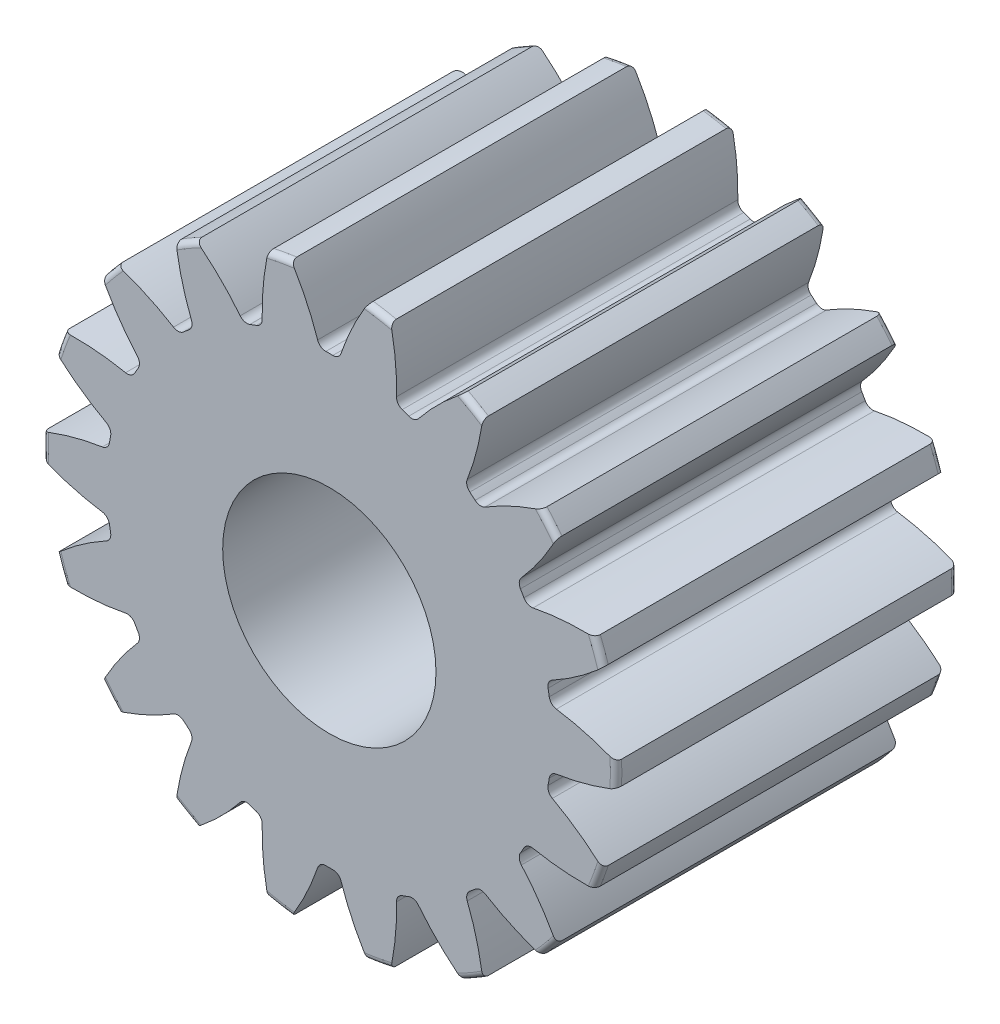
SolidWorks part; units mm, degrees
ref_plane "Front Plane" through (0, 0, 0) normal (0, 0, 1) x (1, 0, 0)
ref_plane "Top Plane" through (0, 0, 0) normal (0, 1, 0) x (1, 0, 0)
ref_plane "Right Plane" through (0, 0, 0) normal (1, 0, 0) x (0, 0, -1)
sketch "Sketch1" plane through (0, 0, 0) normal (0, 0, 1) x (1, 0, 0)
  line L0 (-228.6, 0) -> (228.6, 0) construction
  circle A0 centre (0, 0) radius 5.334 construction
  circle A1 centre (0, 0) radius 4.7625 construction
  circle A2 centre (0, 0) radius 4.1434 construction
  circle A3 centre (0, 0) radius 3.9751 construction
  circle A4 centre (0, 0) radius 1.9844 construction
  dimension "D2" = 0.5715
  dimension "D3" = 1.1906
  dimension "D1" = 1.1906
sketch "Sketch2" plane through (0, 0, 0) normal (1, 0, 0) x (0, 0, -1)
  line L0 (0, 0) -> (-3.175, 0) construction
  line L1 (-3.175, 0) -> (-9.525, 0) construction
  dimension "Overall Width" = 9.525
  dimension "Face Width" = 3.175
sketch "Sketch4" plane through (0, 0, 0) normal (1, 0, 0) x (0, 0, -1)
  line L0 (-9.525, 1.9844) -> (-9.525, 3.9751)
  line L1 (-9.525, 3.9751) -> (-6.35, 3.9751)
  line L2 (-6.35, 3.9751) -> (-6.35, 5.334)
  line L3 (-6.35, 5.334) -> (0, 5.334)
  line L4 (0, 5.334) -> (0, 1.9844)
  line L5 (-6.35, 3.9751) -> (-6.35, 0) construction
  line L6 (0, 5.334) -> (0, -5.334) construction
  line L7 (-6.35, 3.9751) -> (0, 3.9751) construction
  line L12 (-9.525, 1.9844) -> (0, 1.9844)
  dimension "D1" = 6.35
  dimension "D2" = 1.9844
revolve "Revolve1" add sketch "Sketch4" angle 360 about L1
fillet "Fillet2" radius 0.1067 4 edges at (0, 3.9751, 9.525) (0, 3.9751, 6.35) (0, 5.334, 6.35) (0, 5.334, 0)
sketch "Sketch7" plane through (0, 0, 6.35) normal (0, 0, 1) x (1, 0, 0)
  line L0 (0, 0) -> (0, 5.334) construction
  line L1 (0.4151, 4.7444) -> (0.6703, 5.2917) construction
  line L3 (0.9262, 5.253) -> (0.827, 4.6901) construction
  line L4 (0.827, 4.6901) -> (0.7195, 4.0804) construction
  line L5 (0, 0) -> (0.7195, 4.0804) construction
  line L6 (0.4151, 4.7444) -> (0, 0) construction
  line L7 (0.4151, 4.7444) -> (0.4649, 5.3137) construction
  line L8 (0.4151, 4.7444) -> (0, 0) construction
  circle A0 centre (0, 0) radius 5.334 construction
  arc A1 (-0.0648, 4.1429) -> (0.0648, 4.1429) centre (0, 0) cw
  circle A2 centre (0, 0) radius 4.1434 construction
  arc A3 (-0.4151, 4.7444) -> (0.4151, 4.7444) centre (0, 0) cw construction
  circle A4 centre (0, 0) radius 4.7625 construction
  arc A5 (1.139, 5.211) -> (0.712, 5.2863) centre (0, 0) ccw construction
  arc A6 (0.4151, 4.7444) -> (1.2326, 4.6002) centre (0, 0) cw construction
  arc A7 (-0.712, 5.2863) -> (0.712, 5.2863) centre (0, 0) cw
  arc A8 (0.2177, 4.251) -> (0.712, 5.2863) centre (4.7314, 2.7317) cw
  arc A9 (-0.2177, 4.251) -> (-0.712, 5.2863) centre (-4.7314, 2.7317) ccw
  arc A10 (-0.0648, 4.1429) -> (-0.2177, 4.251) centre (-0.0672, 4.3016) cw
  arc A11 (0.0648, 4.1429) -> (0.2177, 4.251) centre (0.0672, 4.3016) ccw
  point P26 (-0.1817, 4.1394)
  point P29 (0.1817, 4.1394)
  dimension "D4" = 0.1588
  dimension "D5" = 4.7625
  dimension "D3" = 20
  dimension "D1" = 1.6624
  dimension "D2" = 0.8312
extrude "Cut-Extrude2" cut sketch "Sketch7" against normal through all
pattern_circular "CirPattern1" count 18 over 360 about axis through (0, 0, 0) along (0, 0, 1) of "Cut-Extrude2"
sketch "Sketch8" plane through (0, 0, 0) normal (0, 1, 0) x (1, 0, 0)
  line L0 (-3.8684, -9.525) -> (3.8684, -9.525) construction
  line L1 (-4.0818, -6.35) -> (4.0818, -6.35)
  line L2 (-4.0818, -6.35) -> (-4.0818, -9.525)
  line L3 (-4.0818, -9.525) -> (4.0818, -9.525)
  line L4 (4.0818, -6.35) -> (4.0818, -9.525)
  line L5 (-4.0818, -6.35) -> (4.0818, -6.35) construction
  point P4 (0, -9.525)
extrude "Cut-Extrude3" cut sketch "Sketch8" against normal through all both and the other way through all
sketch "Sketch9" plane through (0, 0, 0) normal (0, 0, 1) x (1, 0, 0)
  circle A0 centre (0, 0) radius 4.7625
  circle A1 centre (0, 0) radius 4.7625 construction
equation "\"D1@Sketch1\"=2.25*(\"Pitch Dia.@Sketch1\"/\"Number of Teeth@Sketch1\")"
equation "\"D1@CirPattern1\"=\"Number of Teeth@Sketch1\""
equation "\"D1@Fillet2\"=\"OD@Sketch1\"*.01"
equation "\"D1@Sketch7\"=3.14159*(\"Pitch Dia.@Sketch1\"/\"Number of Teeth@Sketch1\")"
equation "\"D2@Sketch7\"=\"D1@Sketch7\"/2"
equation "\"D4@Sketch7\"=\"D1@Sketch7\"*.0955"
equation "\"D5@Sketch7\"=\"Pitch Dia.@Sketch1\"/2"
